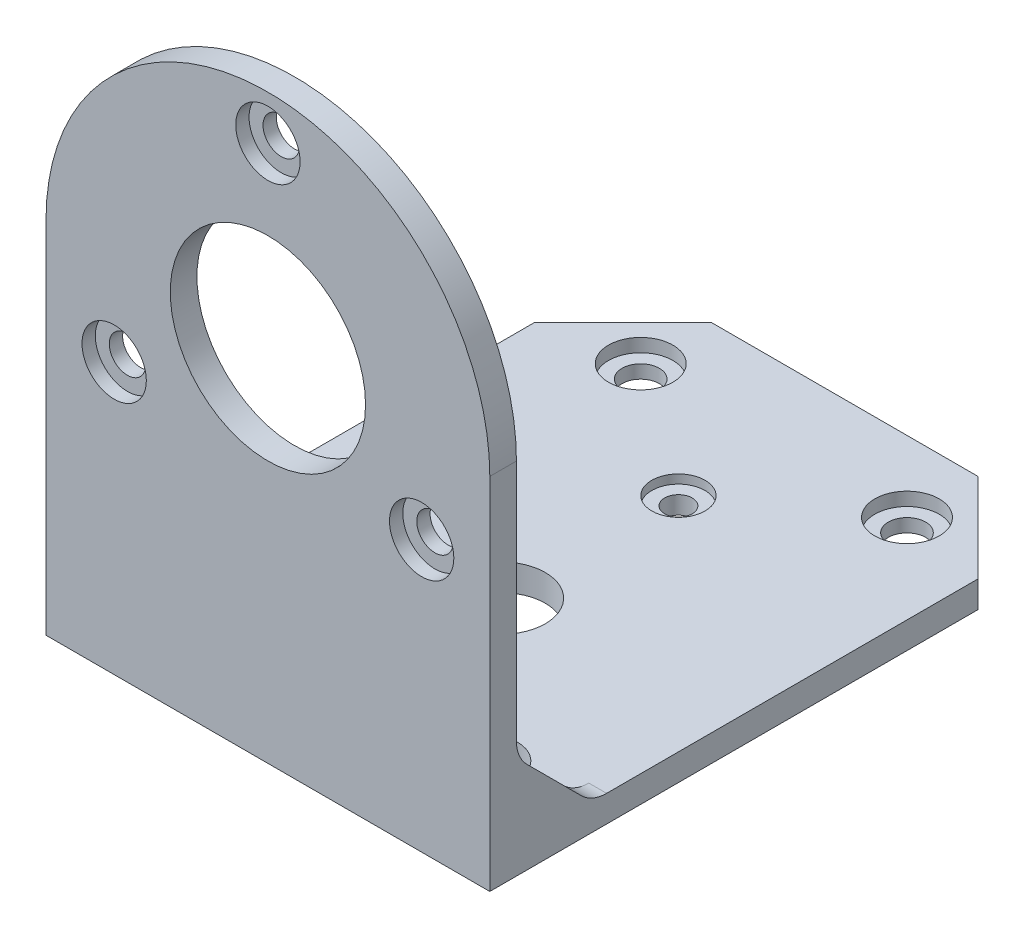
SolidWorks part; units mm, degrees
material "Nylon 101"
ref_plane "前视基准面" through (0, 0, 0) normal (0, 0, 1) x (1, 0, 0)
ref_plane "上视基准面" through (0, 0, 0) normal (0, 1, 0) x (1, 0, 0)
ref_plane "右视基准面" through (0, 0, 0) normal (1, 0, 0) x (0, 0, -1)
sketch "草图1" plane through (0, 0, 0) normal (0, 0, 1) x (1, 0, 0)
  line L0 (0, 0) -> (0, 90) construction
  circle A0 centre (0, 90) radius 11
  arc A2 (19, 72) -> (20, 75) centre (24, 72) cw
  circle A3 centre (0, 90) radius 25
  arc A5 (-19, 72) -> (-20, 75) centre (-24, 72) ccw
  circle A6 centre (0, 110) radius 2.05
  circle A7 centre (17.3205, 80) radius 2.05
  circle A8 centre (-17.3205, 80) radius 2.05
  point P30 (0, 90)
  dimension "D4" = 50
  dimension "D8" = 4.1
  dimension "D2" = 22
  dimension "D10" = 20
  dimension "D12" = 5
  dimension "D9" = 40
  dimension "D11" = 3
extrude "凸台-拉伸1" add sketch "草图1" along normal mid plane 3
sketch "草图3" plane through (0, 0, -1.5) normal (0, 0, -1) x (-1, 0, 0)
  line L0 (-25, 90) -> (-25, 52.5)
  line L1 (-25, 52.5) -> (25, 52.5)
  line L2 (25, 52.5) -> (25, 90)
  circle A0 centre (0, 90) radius 25 construction
  circle A1 centre (0, 90) radius 25 construction
  circle A2 centre (0, 90) radius 25
  circle M5 centre (0, 90) radius 25
  dimension "D1" = 37.5
extrude "凸台-拉伸2" add sketch "草图3" against normal up to surface (3 mm away) contours L0 L1 M5 | L1 L2 M5
sketch "草图4" plane through (0, 0, 1.5) normal (0, 0, 1) x (1, 0, 0)
  line L0 (25, 52.5) -> (25, 49.5)
  line L1 (25, 49.5) -> (-25, 49.5)
  line L2 (-25, 52.5) -> (-25, 49.5)
  line L3 (25, 52.5) -> (-25, 52.5) construction
  line L4 (25, 52.5) -> (-25, 52.5)
  dimension "D1" = 3
extrude "凸台-拉伸3" add sketch "草图4" against normal blind 65
sketch "草图6" plane through (0, 52.5, 0) normal (0, 1, 0) x (1, 0, 0)
  line L0 (-15, 63.5) -> (-25, 53.5)
  line L1 (25, 53.5) -> (15, 63.5)
  line L4 (-25, 1.5) -> (25, 1.5)
  line L5 (25, 1.5) -> (25, 63.5)
  line L6 (25, 63.5) -> (-25, 63.5)
  line L7 (-25, 63.5) -> (-25, 1.5)
  line L8 (-25, 1.5) -> (25, 1.5)
  line L9 (25, 1.5) -> (25, 53.5)
  line L10 (15, 63.5) -> (-15, 63.5)
  line L11 (-25, 53.5) -> (-25, 1.5)
  line M8 (25, 1.5) -> (25, 63.5)
  line M9 (25, 63.5) -> (-25, 63.5)
  line M10 (-25, 63.5) -> (-25, 1.5)
  dimension "D1" = 0
extrude "切除-拉伸1" cut sketch "草图6" against normal blind 55 contours L0 M9 M10 | L1 M8 M9
sketch "草图7" plane through (0, 52.5, 0) normal (0, 1, 0) x (1, 0, 0)
  line L0 (0, 0) -> (0, 63.5) construction
  line L1 (15, 63.5) -> (-15, 63.5) construction
  line L2 (-25, 53.5) -> (-25, 1.5) construction
  line L3 (-15, 55.5) -> (15, 55.5) construction
  line L4 (-15, 55.5) -> (-15, 8) construction
  line L5 (-15, 8) -> (15, 8) construction
  line L6 (15, 55.5) -> (15, 8) construction
  line L7 (-15, 55.5) -> (15, 8) construction
  line L8 (-15, 8) -> (15, 55.5) construction
  circle A0 centre (-15, 55.5) radius 2.1
  circle A1 centre (15, 55.5) radius 2.1
  circle A2 centre (15, 8) radius 2.1
  circle A3 centre (-15, 8) radius 2.1
  point P5 (0, 31.75)
  dimension "D3" = 4.2
  dimension "D4" = 4.2
  dimension "D5" = 4.2
  dimension "D6" = 4.2
  dimension "D1" = 8
  dimension "D2" = 10
  dimension "D7" = 47.5
  dimension "D8" = 30
extrude "切除-拉伸2" cut sketch "草图7" against normal blind 55
sketch "草图9" plane through (0, 52.5, 0) normal (0, 1, 0) x (1, 0, 0)
  circle A0 centre (-15, 55.5) radius 3.625
  circle A1 centre (15, 55.5) radius 3.625
  circle A2 centre (15, 8) radius 3.625
  circle A3 centre (-15, 8) radius 3.625
  dimension "D1" = 7.25
  dimension "D2" = 7.25
  dimension "D3" = 7.25
  dimension "D4" = 7.25
extrude "切除-拉伸3" cut sketch "草图9" against normal blind 1.5
sketch "草图10" plane through (0, 52.5, 0) normal (0, 1, 0) x (1, 0, 0)
  line L0 (-25, 24.75) -> (25, 24.75) construction
  line L1 (-25, 53.5) -> (-25, 1.5) construction
  line L2 (25, 53.5) -> (25, 1.5) construction
  line L3 (25, 1.5) -> (-25, 1.5) construction
  line L4 (0, 24.75) -> (0, 50.696) construction
  dimension "D1" = 23.25
sketch "草图11" plane through (0, 0, 1.5) normal (0, 0, 1) x (1, 0, 0)
  circle A0 centre (0, 110) radius 2.05 construction
  circle A1 centre (0, 110) radius 2.05
  circle A2 centre (-17.3205, 80) radius 2.05 construction
  circle A3 centre (-17.3205, 80) radius 2.05
  circle A4 centre (17.3205, 80) radius 2.05 construction
  circle A5 centre (17.3205, 80) radius 2.05
  circle A6 centre (0, 110) radius 3.625
  circle A7 centre (17.3205, 80) radius 3.625
  circle A8 centre (-17.3205, 80) radius 3.625
  dimension "D1" = 7.25
  dimension "D2" = 7.25
  dimension "D3" = 7.25
extrude "切除-拉伸4" cut sketch "草图11" against normal blind 1.5
sketch "草图12" plane through (0, 49.5, 0) normal (0, -1, 0) x (1, 0, 0)
  circle A0 centre (0, -4.75) radius 1.55 construction
  circle A1 centre (0, -4.75) radius 1.55
  circle A2 centre (0, -44.75) radius 1.55 construction
  circle A3 centre (0, -44.75) radius 1.55
  circle A4 centre (0, -24.75) radius 5 construction
  circle A5 centre (0, -24.75) radius 5
extrude "切除-拉伸5" cut sketch "草图12" against normal blind 6.5
sketch "草图13" plane through (0, 52.5, 0) normal (0, 1, 0) x (1, 0, 0)
  circle A0 centre (0, 44.75) radius 3
  circle A1 centre (0, 4.75) radius 3
  circle M1 centre (0, 4.75) radius 1.55
  circle M2 centre (0, 44.75) radius 1.55
  dimension "D1" = 6
  dimension "D2" = 6
extrude "切除-拉伸13" cut sketch "草图13" against normal offset from surface (1 mm away) 2 contours A1 M1 | A0 M2 up to face at (1.55, 49.5, -4.75)
sketch "草图14" plane through (25, 0, 0) normal (1, 0, 0) x (0, 0, -1)
  line L0 (1.5, 61) -> (10, 52.5)
  line L2 (53.5, 52.5) -> (1.5, 52.5) construction
  line L4 (1.5, 52.5) -> (10, 52.5)
  line L5 (1.5, 90) -> (1.5, 52.5) construction
  line L6 (1.5, 52.5) -> (1.5, 61)
  dimension "D1" = 8.5
  dimension "D2" = 45
extrude "凸台-拉伸4" add sketch "草图14" against normal blind 2
fillet "圆角1" radius 4 2 edges at (24, 52.5, -10) (24, 61, -1.5)
mirror "镜向1" about plane through (0, 0, 0) normal (1, 0, 0) of "圆角1", "凸台-拉伸4"
